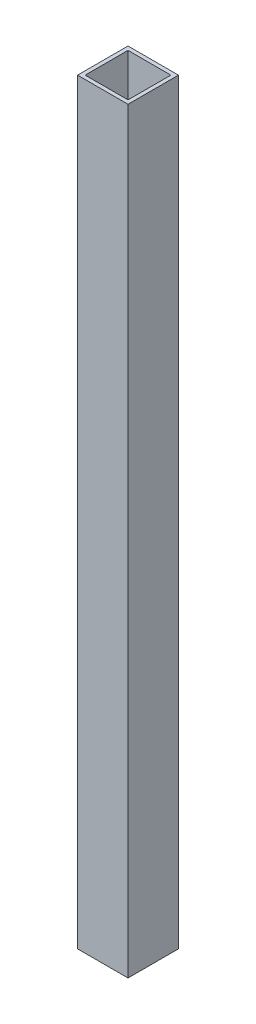
SolidWorks part; units mm, degrees
ref_plane "Спереди" through (0, 0, 0) normal (0, 0, 1) x (1, 0, 0)
ref_plane "Сверху" through (0, 0, 0) normal (0, 1, 0) x (1, 0, 0)
ref_plane "Справа" through (0, 0, 0) normal (1, 0, 0) x (0, 0, -1)
sketch "Эскиз1" plane through (0, 0, 0) normal (0, 1, 0) x (1, 0, 0)
  line L1 (-10, -10) -> (10, -10)
  line L2 (-10, -10) -> (-10, 10)
  line L3 (-10, 10) -> (10, 10)
  line L4 (10, -10) -> (10, 10)
  line L5 (-10, -10) -> (10, 10) construction
  line L6 (-10, 10) -> (10, -10) construction
  line L7 (-8.5, -8.5) -> (8.5, -8.5)
  line L8 (-8.5, -8.5) -> (-8.5, 8.5)
  line L9 (-8.5, 8.5) -> (8.5, 8.5)
  line L10 (8.5, -8.5) -> (8.5, 8.5)
  line L11 (-8.5, -8.5) -> (8.5, 8.5) construction
  line L12 (-8.5, 8.5) -> (8.5, -8.5) construction
  point P0 (0, 0)
  point P5 (0, 0)
  dimension "D1" = 20
  dimension "D2" = 1.5
extrude "Бобышка-Вытянуть1" add sketch "Эскиз1" along normal blind 300
